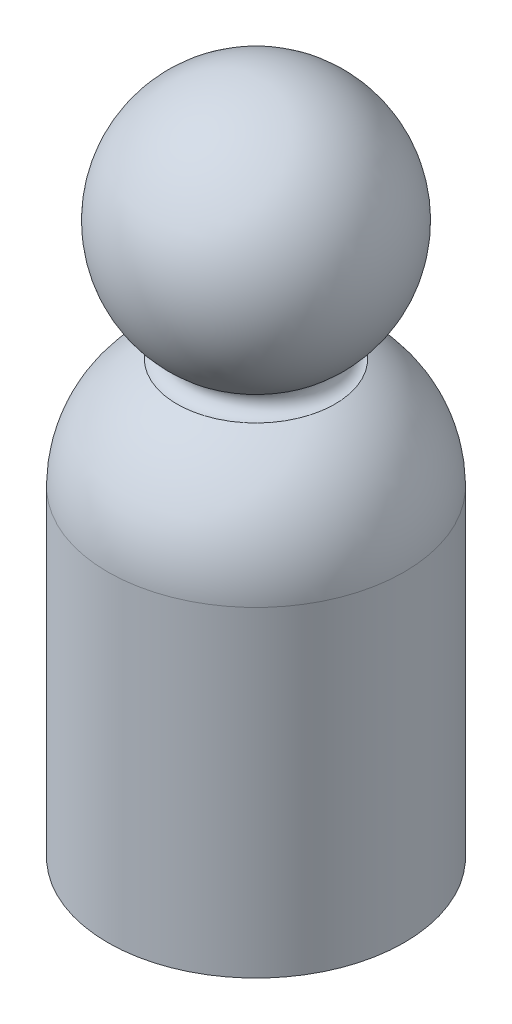
SolidWorks part; units mm, degrees
material "Mahogany"
ref_plane "Front" through (0, 0, 0) normal (0, 0, 1) x (1, 0, 0)
ref_plane "Top" through (0, 0, 0) normal (0, 1, 0) x (1, 0, 0)
ref_plane "Right" through (0, 0, 0) normal (1, 0, 0) x (0, 0, -1)
sketch "Sketch1" plane through (0, 0, 0) normal (0, 0, 1) x (1, 0, 0)
  line L0 (0, 0) -> (0, 44.6637) construction
  line L1 (0, 0) -> (-12, 0)
  line L2 (-12, 0) -> (-12, 26)
  line L3 (0, 54.6637) -> (0, 44.6637) construction
  line L4 (0, 0) -> (0, 54.6637)
  arc A0 (0, 54.6637) -> (-6.4, 36.98) centre (0, 44.6637) ccw
  arc A1 (-12, 26) -> (-6.4, 34.98) centre (-2, 26) cw
  arc A2 (-6.4, 34.98) -> (-6.4, 36.98) centre (-6.4, 35.98) ccw
  dimension "D1" = 10
  dimension "D2" = 6.4
  dimension "D4" = 10
  dimension "D5" = 1
  dimension "D3" = 26
  dimension "D6" = 24
  dimension "D7" = 2
revolve "Revolve1" add sketch "Sketch1" angle 360 about L4
